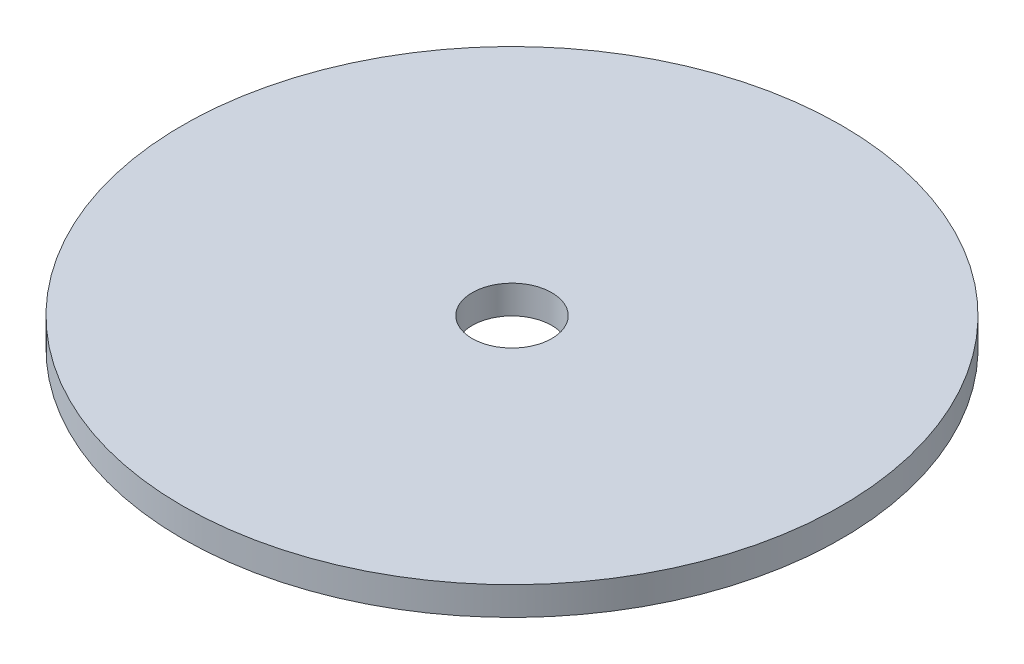
SolidWorks part; units mm, degrees
material "PVC Rigid"
ref_plane "Front Plane" through (0, 0, 0) normal (0, 0, 1) x (1, 0, 0)
ref_plane "Top Plane" through (0, 0, 0) normal (0, 1, 0) x (1, 0, 0)
ref_plane "Right Plane" through (0, 0, 0) normal (1, 0, 0) x (0, 0, -1)
sketch "Sketch1" plane through (0, 0, 0) normal (0, 1, 0) x (1, 0, 0)
  circle A0 centre (0, 0) radius 29
  circle A1 centre (0, 0) radius 3.5
  dimension "D1" = 58
  dimension "D2" = 7
extrude "Boss-Extrude1" add sketch "Sketch1" along normal blind 2.5
